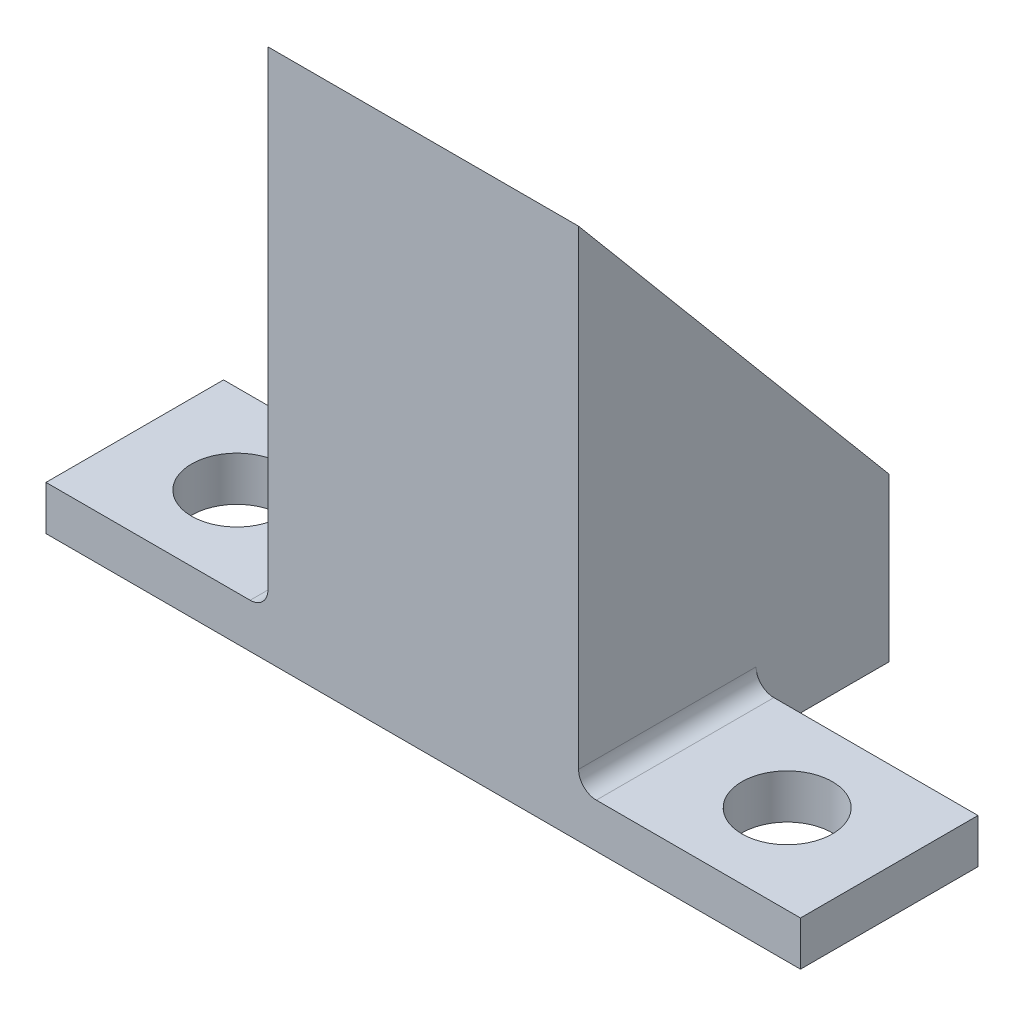
SolidWorks part; units mm, degrees
ref_plane "Front Plane" through (0, 0, 0) normal (0, 0, 1) x (1, 0, 0)
ref_plane "Top Plane" through (0, 0, 0) normal (0, 1, 0) x (1, 0, 0)
ref_plane "Right Plane" through (0, 0, 0) normal (1, 0, 0) x (0, 0, -1)
sketch "Sketch1" plane through (0, 0, 0) normal (0, 1, 0) x (1, 0, 0)
  line L1 (0, 0) -> (44.45, 0)
  line L2 (0, 0) -> (0, 88.9)
  line L3 (0, 88.9) -> (44.45, 88.9)
  line L4 (44.45, 0) -> (44.45, 88.9)
  dimension "D1" = 44.45
  dimension "D2" = 88.9
extrude "Boss-Extrude1" add sketch "Sketch1" along normal blind 76.2
sketch "Sketch2" plane through (44.45, 0, 0) normal (1, 0, 0) x (0, 0, -1)
  line L1 (44.45, 0) -> (0, 0)
  line L2 (0, 0) -> (0, 76.2)
  line L3 (0, 76.2) -> (44.45, 23.2266)
  line L4 (44.45, 23.2266) -> (44.45, 0)
  dimension "D1" = 50
  dimension "D2" = 44.45
extrude "Cut-Extrude1" cut sketch "Sketch2" against normal blind 76.2
sketch "Sketch3" plane through (44.45, 0, 0) normal (1, 0, 0) x (0, 0, -1)
  line L1 (0, 0) -> (25.4, 0)
  line L2 (0, 0) -> (0, 6.35)
  line L3 (0, 6.35) -> (25.4, 6.35)
  line L4 (25.4, 0) -> (25.4, 6.35)
  dimension "D1" = 25.4
  dimension "D2" = 6.35
extrude "Boss-Extrude2" add sketch "Sketch3" along normal blind 31.75
fillet "Fillet1" radius 2.54 1 edges at (44.45, 6.35, -12.7)
sketch "Sketch4" plane through (0, 6.35, 0) normal (0, 1, 0) x (1, 0, 0)
  line L0 (76.2, 25.4) -> (76.2, 0) construction
  line L1 (76.2, 25.4) -> (46.99, 25.4) construction
  circle A0 centre (61.595, 12.7) radius 6.477
  point P2 (0, 0)
  point P3 (0, 0)
  point P6 (76.2, 12.7)
  point P9 (61.595, 25.4)
  dimension "D1" = 12.954
extrude "Cut-Extrude2" cut sketch "Sketch4" against normal blind 38.1
ref_plane "Plane1" through (22.225, 0, 0) normal (1, 0, 0) x (0, 0, -1)
sketch "Sketch5" plane through (0, 0, 0) normal (-1, 0, 0) x (0, 0, 1)
  line L1 (0, 0) -> (-25.4, 0)
  line L2 (0, 0) -> (0, 6.35)
  line L3 (0, 6.35) -> (-25.4, 6.35)
  line L4 (-25.4, 0) -> (-25.4, 6.35)
  dimension "D1" = 6.35
  dimension "D2" = 25.4
extrude "Boss-Extrude3" add sketch "Sketch5" along normal blind 31.75
mirror "Mirror4" about plane through (22.225, 0, 0) normal (1, 0, 0) of "Cut-Extrude2"
fillet "Fillet2" radius 2.54 1 edges at (0, 6.35, -12.7)
